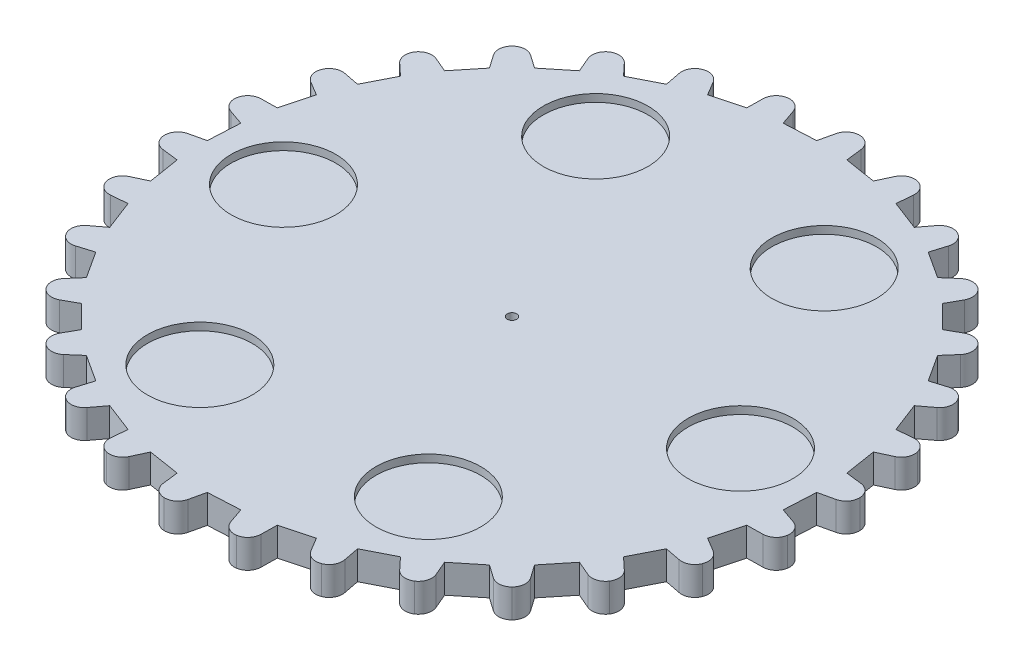
SolidWorks part; units mm, degrees
ref_plane "Front Plane" through (0, 0, 0) normal (0, 0, 1) x (1, 0, 0)
ref_plane "Top Plane" through (0, 0, 0) normal (0, 1, 0) x (1, 0, 0)
ref_plane "Right Plane" through (0, 0, 0) normal (1, 0, 0) x (0, 0, -1)
sketch "Sketch2" plane through (0, 0, 0) normal (0, 1, 0) x (1, 0, 0)
  line L0 (0, 0) -> (0, 203.2)
  line L1 (0, 0) -> (42.2477, 198.7596)
  line L2 (0, 203.2) -> (2.4314, 213.7315)
  line L3 (11.5588, 220.6095) -> (11.5645, 220.6092)
  line L4 (19.923, 212.8148) -> (21.2402, 202.0868)
  line L5 (0, 0) -> (21.2402, 202.0868)
  line L6 (21.2402, 202.0868) -> (42.2477, 198.7596)
  line L7 (57.1735, 213.3854) -> (57.179, 213.3839)
  line L8 (42.2477, 198.7596) -> (46.8155, 208.5554)
  line L9 (63.7343, 204.0221) -> (62.7923, 193.2547)
  line L10 (62.7923, 193.2547) -> (82.6489, 185.6324)
  line L11 (100.2894, 196.8354) -> (100.2945, 196.8328)
  line L12 (82.6489, 185.6324) -> (89.1536, 194.2645)
  line L13 (104.7601, 186.3126) -> (101.6, 175.9764)
  line L14 (101.6, 175.9764) -> (119.438, 164.3923)
  line L15 (139.0223, 171.6827) -> (139.0267, 171.6791)
  line L16 (119.438, 164.3923) -> (127.5952, 171.4833)
  line L17 (141.2074, 160.4604) -> (135.9673, 151.007)
  line L18 (135.9673, 151.007) -> (151.007, 135.9673)
  line L19 (171.6791, 139.0267) -> (171.6827, 139.0223)
  line L20 (151.007, 135.9673) -> (160.4604, 141.2074)
  line L21 (171.4833, 127.5952) -> (164.3923, 119.438)
  line L22 (164.3923, 119.438) -> (175.9764, 101.6)
  line L23 (196.8328, 100.2945) -> (196.8354, 100.2894)
  line L24 (175.9764, 101.6) -> (186.3126, 104.7601)
  line L25 (194.2645, 89.1536) -> (185.6324, 82.6489)
  line L26 (185.6324, 82.6489) -> (193.2547, 62.7923)
  line L27 (213.3839, 57.179) -> (213.3854, 57.1735)
  line L28 (193.2547, 62.7923) -> (204.0221, 63.7343)
  line L29 (208.5554, 46.8155) -> (198.7596, 42.2477)
  line L30 (198.7596, 42.2477) -> (202.0868, 21.2402)
  line L31 (220.6092, 11.5645) -> (220.6095, 11.5588)
  line L32 (202.0868, 21.2402) -> (212.8148, 19.923)
  line L33 (213.7315, 2.4314) -> (203.2, 0)
  line L34 (203.2, 0) -> (202.0868, -21.2402)
  line L35 (218.1927, -34.5554) -> (218.1918, -34.5611)
  line L36 (202.0868, -21.2402) -> (212.3065, -24.7591)
  line L37 (209.5664, -42.059) -> (198.7596, -42.2477)
  line L38 (198.7596, -42.2477) -> (193.2547, -62.7923)
  line L39 (206.2402, -79.1652) -> (206.2382, -79.1705)
  line L40 (193.2547, -62.7923) -> (202.5194, -68.359)
  line L41 (196.2424, -84.7112) -> (185.6324, -82.6489)
  line L42 (185.6324, -82.6489) -> (175.9764, -101.6)
  line L43 (185.274, -120.315) -> (185.2709, -120.3197)
  line L44 (175.9764, -101.6) -> (183.8812, -108.9714)
  line L45 (174.3415, -123.6612) -> (164.3923, -119.438)
  line L46 (164.3923, -119.438) -> (151.007, -135.9673)
  line L47 (156.2104, -156.2064) -> (156.2064, -156.2104)
  line L48 (151.007, -135.9673) -> (157.2065, -144.8211)
  line L49 (144.8211, -157.2065) -> (135.9673, -151.007)
  line L50 (135.9673, -151.007) -> (119.438, -164.3923)
  line L51 (120.3197, -185.2709) -> (120.315, -185.274)
  line L52 (119.438, -164.3923) -> (123.6612, -174.3415)
  line L53 (108.9714, -183.8812) -> (101.6, -175.9764)
  line L54 (101.6, -175.9764) -> (82.6489, -185.6324)
  line L55 (79.1705, -206.2382) -> (79.1652, -206.2402)
  line L56 (82.6489, -185.6324) -> (84.7112, -196.2424)
  line L57 (68.359, -202.5194) -> (62.7923, -193.2547)
  line L58 (62.7923, -193.2547) -> (42.2477, -198.7596)
  line L59 (34.5611, -218.1918) -> (34.5554, -218.1927)
  line L60 (42.2477, -198.7596) -> (42.059, -209.5664)
  line L61 (24.7591, -212.3065) -> (21.2402, -202.0868)
  line L62 (21.2402, -202.0868) -> (0, -203.2)
  line L63 (-11.5588, -220.6095) -> (-11.5645, -220.6092)
  line L64 (0, -203.2) -> (-2.4314, -213.7315)
  line L65 (-19.923, -212.8148) -> (-21.2402, -202.0868)
  line L66 (-21.2402, -202.0868) -> (-42.2477, -198.7596)
  line L67 (-57.1735, -213.3854) -> (-57.179, -213.3839)
  line L68 (-42.2477, -198.7596) -> (-46.8155, -208.5554)
  line L69 (-63.7343, -204.0221) -> (-62.7923, -193.2547)
  line L70 (-62.7923, -193.2547) -> (-82.6489, -185.6324)
  line L71 (-100.2894, -196.8354) -> (-100.2945, -196.8328)
  line L72 (-82.6489, -185.6324) -> (-89.1536, -194.2645)
  line L73 (-104.7601, -186.3126) -> (-101.6, -175.9764)
  line L74 (-101.6, -175.9764) -> (-119.438, -164.3923)
  line L75 (-139.0223, -171.6827) -> (-139.0267, -171.6791)
  line L76 (-119.438, -164.3923) -> (-127.5952, -171.4833)
  line L77 (-141.2074, -160.4604) -> (-135.9673, -151.007)
  line L78 (-135.9673, -151.007) -> (-151.007, -135.9673)
  line L79 (-171.6791, -139.0267) -> (-171.6827, -139.0223)
  line L80 (-151.007, -135.9673) -> (-160.4604, -141.2074)
  line L81 (-171.4833, -127.5952) -> (-164.3923, -119.438)
  line L82 (-164.3923, -119.438) -> (-175.9764, -101.6)
  line L83 (-196.8328, -100.2945) -> (-196.8354, -100.2894)
  line L84 (-175.9764, -101.6) -> (-186.3126, -104.7601)
  line L85 (-194.2645, -89.1536) -> (-185.6324, -82.6489)
  line L86 (-185.6324, -82.6489) -> (-193.2547, -62.7923)
  line L87 (-213.3839, -57.179) -> (-213.3854, -57.1735)
  line L88 (-193.2547, -62.7923) -> (-204.0221, -63.7343)
  line L89 (-208.5554, -46.8155) -> (-198.7596, -42.2477)
  line L90 (-198.7596, -42.2477) -> (-202.0868, -21.2402)
  line L91 (-220.6092, -11.5645) -> (-220.6095, -11.5588)
  line L92 (-202.0868, -21.2402) -> (-212.8148, -19.923)
  line L93 (-213.7315, -2.4314) -> (-203.2, 0)
  line L94 (-203.2, 0) -> (-202.0868, 21.2402)
  line L95 (-218.1927, 34.5554) -> (-218.1918, 34.5611)
  line L96 (-202.0868, 21.2402) -> (-212.3065, 24.7591)
  line L97 (-209.5664, 42.059) -> (-198.7596, 42.2477)
  line L98 (-198.7596, 42.2477) -> (-193.2547, 62.7923)
  line L99 (-206.2402, 79.1652) -> (-206.2382, 79.1705)
  line L100 (-193.2547, 62.7923) -> (-202.5194, 68.359)
  line L101 (-196.2424, 84.7112) -> (-185.6324, 82.6489)
  line L102 (-185.6324, 82.6489) -> (-175.9764, 101.6)
  line L103 (-185.274, 120.315) -> (-185.2709, 120.3197)
  line L104 (-175.9764, 101.6) -> (-183.8812, 108.9714)
  line L105 (-174.3415, 123.6612) -> (-164.3923, 119.438)
  line L106 (-164.3923, 119.438) -> (-151.007, 135.9673)
  line L107 (-156.2104, 156.2064) -> (-156.2064, 156.2104)
  line L108 (-151.007, 135.9673) -> (-157.2065, 144.8211)
  line L109 (-144.8211, 157.2065) -> (-135.9673, 151.007)
  line L110 (-135.9673, 151.007) -> (-119.438, 164.3923)
  line L111 (-120.3197, 185.2709) -> (-120.315, 185.274)
  line L112 (-119.438, 164.3923) -> (-123.6612, 174.3415)
  line L113 (-108.9714, 183.8812) -> (-101.6, 175.9764)
  line L114 (-101.6, 175.9764) -> (-82.6489, 185.6324)
  line L115 (-79.1705, 206.2382) -> (-79.1652, 206.2402)
  line L116 (-82.6489, 185.6324) -> (-84.7112, 196.2424)
  line L117 (-68.359, 202.5194) -> (-62.7923, 193.2547)
  line L118 (-62.7923, 193.2547) -> (-42.2477, 198.7596)
  line L119 (-34.5611, 218.1918) -> (-34.5554, 218.1927)
  line L120 (-42.2477, 198.7596) -> (-42.059, 209.5664)
  line L121 (-24.7591, 212.3065) -> (-21.2402, 202.0868)
  line L122 (-21.2402, 202.0868) -> (0, 203.2)
  arc A1 (11.5645, 220.6092) -> (19.923, 212.8148) centre (11.0992, 211.7314) cw
  arc A2 (11.5588, 220.6095) -> (2.4314, 213.7315) centre (11.0935, 211.7317) ccw
  arc A3 (57.1735, 213.3854) -> (46.8155, 208.5554) centre (54.8726, 204.7983) ccw
  arc A4 (57.179, 213.3839) -> (63.7343, 204.0221) centre (54.8781, 204.7969) cw
  arc A5 (100.2894, 196.8354) -> (89.1536, 194.2645) centre (96.2535, 188.9144) ccw
  arc A6 (100.2945, 196.8328) -> (104.7601, 186.3126) centre (96.2586, 188.9118) cw
  arc A7 (139.0223, 171.6827) -> (127.5952, 171.4833) centre (133.4276, 164.7739) ccw
  arc A8 (139.0267, 171.6791) -> (141.2074, 160.4604) centre (133.432, 164.7703) cw
  arc A9 (171.6791, 139.0267) -> (160.4604, 141.2074) centre (164.7703, 133.432) ccw
  arc A10 (171.6827, 139.0223) -> (171.4833, 127.5952) centre (164.7739, 133.4276) cw
  arc A11 (196.8328, 100.2945) -> (186.3126, 104.7601) centre (188.9118, 96.2586) ccw
  arc A12 (196.8354, 100.2894) -> (194.2645, 89.1536) centre (188.9144, 96.2535) cw
  arc A13 (213.3839, 57.179) -> (204.0221, 63.7343) centre (204.7969, 54.8781) ccw
  arc A14 (213.3854, 57.1735) -> (208.5554, 46.8155) centre (204.7983, 54.8726) cw
  arc A15 (220.6092, 11.5645) -> (212.8148, 19.923) centre (211.7314, 11.0992) ccw
  arc A16 (220.6095, 11.5588) -> (213.7315, 2.4314) centre (211.7317, 11.0935) cw
  arc A17 (218.1927, -34.5554) -> (212.3065, -24.7591) centre (209.4122, -33.1647) ccw
  arc A18 (218.1918, -34.5611) -> (209.5664, -42.059) centre (209.4113, -33.1704) cw
  arc A19 (206.2402, -79.1652) -> (202.5194, -68.359) centre (197.9407, -75.9793) ccw
  arc A20 (206.2382, -79.1705) -> (196.2424, -84.7112) centre (197.9386, -75.9846) cw
  arc A21 (185.274, -120.315) -> (183.8812, -108.9714) centre (177.8182, -115.4731) ccw
  arc A22 (185.2709, -120.3197) -> (174.3415, -123.6612) centre (177.8151, -115.4779) cw
  arc A23 (156.2104, -156.2064) -> (157.2065, -144.8211) centre (149.9243, -149.9202) ccw
  arc A24 (156.2064, -156.2104) -> (144.8211, -157.2065) centre (149.9202, -149.9243) cw
  arc A25 (120.3197, -185.2709) -> (123.6612, -174.3415) centre (115.4779, -177.8151) ccw
  arc A26 (120.315, -185.274) -> (108.9714, -183.8812) centre (115.4731, -177.8182) cw
  arc A27 (79.1705, -206.2382) -> (84.7112, -196.2424) centre (75.9846, -197.9386) ccw
  arc A28 (79.1652, -206.2402) -> (68.359, -202.5194) centre (75.9793, -197.9407) cw
  arc A29 (34.5611, -218.1918) -> (42.059, -209.5664) centre (33.1704, -209.4113) ccw
  arc A30 (34.5554, -218.1927) -> (24.7591, -212.3065) centre (33.1647, -209.4122) cw
  arc A31 (-11.5588, -220.6095) -> (-2.4314, -213.7315) centre (-11.0935, -211.7317) ccw
  arc A32 (-11.5645, -220.6092) -> (-19.923, -212.8148) centre (-11.0992, -211.7314) cw
  arc A33 (-57.1735, -213.3854) -> (-46.8155, -208.5554) centre (-54.8726, -204.7983) ccw
  arc A34 (-57.179, -213.3839) -> (-63.7343, -204.0221) centre (-54.8781, -204.7969) cw
  arc A35 (-100.2894, -196.8354) -> (-89.1536, -194.2645) centre (-96.2535, -188.9144) ccw
  arc A36 (-100.2945, -196.8328) -> (-104.7601, -186.3126) centre (-96.2586, -188.9118) cw
  arc A37 (-139.0223, -171.6827) -> (-127.5952, -171.4833) centre (-133.4276, -164.7739) ccw
  arc A38 (-139.0267, -171.6791) -> (-141.2074, -160.4604) centre (-133.432, -164.7703) cw
  arc A39 (-171.6791, -139.0267) -> (-160.4604, -141.2074) centre (-164.7703, -133.432) ccw
  arc A40 (-171.6827, -139.0223) -> (-171.4833, -127.5952) centre (-164.7739, -133.4276) cw
  arc A41 (-196.8328, -100.2945) -> (-186.3126, -104.7601) centre (-188.9118, -96.2586) ccw
  arc A42 (-196.8354, -100.2894) -> (-194.2645, -89.1536) centre (-188.9144, -96.2535) cw
  arc A43 (-213.3839, -57.179) -> (-204.0221, -63.7343) centre (-204.7969, -54.8781) ccw
  arc A44 (-213.3854, -57.1735) -> (-208.5554, -46.8155) centre (-204.7983, -54.8726) cw
  arc A45 (-220.6092, -11.5645) -> (-212.8148, -19.923) centre (-211.7314, -11.0992) ccw
  arc A46 (-220.6095, -11.5588) -> (-213.7315, -2.4314) centre (-211.7317, -11.0935) cw
  arc A47 (-218.1927, 34.5554) -> (-212.3065, 24.7591) centre (-209.4122, 33.1647) ccw
  arc A48 (-218.1918, 34.5611) -> (-209.5664, 42.059) centre (-209.4113, 33.1704) cw
  arc A49 (-206.2402, 79.1652) -> (-202.5194, 68.359) centre (-197.9407, 75.9793) ccw
  arc A50 (-206.2382, 79.1705) -> (-196.2424, 84.7112) centre (-197.9386, 75.9846) cw
  arc A51 (-185.274, 120.315) -> (-183.8812, 108.9714) centre (-177.8182, 115.4731) ccw
  arc A52 (-185.2709, 120.3197) -> (-174.3415, 123.6612) centre (-177.8151, 115.4779) cw
  arc A53 (-156.2104, 156.2064) -> (-157.2065, 144.8211) centre (-149.9243, 149.9202) ccw
  arc A54 (-156.2064, 156.2104) -> (-144.8211, 157.2065) centre (-149.9202, 149.9243) cw
  arc A55 (-120.3197, 185.2709) -> (-123.6612, 174.3415) centre (-115.4779, 177.8151) ccw
  arc A56 (-120.315, 185.274) -> (-108.9714, 183.8812) centre (-115.4731, 177.8182) cw
  arc A57 (-79.1705, 206.2382) -> (-84.7112, 196.2424) centre (-75.9846, 197.9386) ccw
  arc A58 (-79.1652, 206.2402) -> (-68.359, 202.5194) centre (-75.9793, 197.9407) cw
  arc A59 (-34.5611, 218.1918) -> (-42.059, 209.5664) centre (-33.1704, 209.4113) ccw
  arc A60 (-34.5554, 218.1927) -> (-24.7591, 212.3065) centre (-33.1647, 209.4122) cw
  point P305 (0, 0)
  dimension "D8" = 8.89
  dimension "D2" = 12
  dimension "D3" = 6
  dimension "D4" = 87
  dimension "D5" = 0
  dimension "D6" = 80
  dimension "D7" = 80
  dimension "D9" = 30
extrude "Boss-Extrude2" add sketch "Sketch2" along normal blind 19.05 contours L3 A2 L2 L0 L5 L4 A1 | L6 L5 L1 | A60 L119 A59 L120 L118 L117 A58 L115 A57 L116 L114 L113 A56 L111 A55 L112 L110 L109 A54 L107 A53 L108 L106 L105 A52 L103 A51 L104 L102 L101 A50 L99 A49 L100 L98 L97 A48 L95 A47 L96 L94 L93 A46 L91 A45 L92 L90 L89 A44 L87 A43
sketch "Sketch3" plane through (0, 19.05, 0) normal (0, 1, 0) x (1, 0, 0)
  circle A0 centre (-152.4, 0) radius 34.925
  circle A1 centre (-76.2, 131.9823) radius 34.925
  circle A2 centre (76.2, 131.9823) radius 34.925
  circle A3 centre (152.4, 0) radius 34.925
  circle A4 centre (76.2, -131.9823) radius 34.925
  circle A5 centre (-76.2, -131.9823) radius 34.925
  point P16 (0, 0)
  dimension "D2" = 69.85
  dimension "D1" = 152.4
  dimension "D3" = 6
extrude "Cut-Extrude1" cut sketch "Sketch3" against normal blind 5.08
sketch "Sketch4" plane through (0, 19.05, 0) normal (0, 1, 0) x (1, 0, 0)
  circle A0 centre (0, 0) radius 3.175
  dimension "D1" = 6.35
extrude "Cut-Extrude2" cut sketch "Sketch4" against normal through all
sketch "Sketch5" plane through (0, 19.05, 0) normal (0, 1, 0) x (1, 0, 0)
  line L120 (46.8155, 208.5554) -> (42.2477, 198.7596)
  line L121 (42.2477, 198.7596) -> (21.2402, 202.0868)
  line L122 (21.2402, 202.0868) -> (19.923, 212.8148)
  line L123 (11.5645, 220.6092) -> (11.5588, 220.6095)
  line L124 (2.4314, 213.7315) -> (0, 203.2)
  line L125 (0, 203.2) -> (-21.2402, 202.0868)
  line L126 (-21.2402, 202.0868) -> (-24.7591, 212.3065)
  line L127 (-34.5554, 218.1927) -> (-34.5611, 218.1918)
  line L128 (-42.059, 209.5664) -> (-42.2477, 198.7596)
  line L129 (-42.2477, 198.7596) -> (-62.7923, 193.2547)
  line L130 (-62.7923, 193.2547) -> (-68.359, 202.5194)
  line L131 (-79.1652, 206.2402) -> (-79.1705, 206.2382)
  line L132 (-84.7112, 196.2424) -> (-82.6489, 185.6324)
  line L133 (-82.6489, 185.6324) -> (-101.6, 175.9764)
  line L134 (-101.6, 175.9764) -> (-108.9714, 183.8812)
  line L135 (-120.315, 185.274) -> (-120.3197, 185.2709)
  line L136 (-123.6612, 174.3415) -> (-119.438, 164.3923)
  line L137 (-119.438, 164.3923) -> (-135.9673, 151.007)
  line L138 (-135.9673, 151.007) -> (-144.8211, 157.2065)
  line L139 (-156.2064, 156.2104) -> (-156.2104, 156.2064)
  line L140 (-157.2065, 144.8211) -> (-151.007, 135.9673)
  line L141 (-151.007, 135.9673) -> (-164.3923, 119.438)
  line L142 (-164.3923, 119.438) -> (-174.3415, 123.6612)
  line L143 (-185.2709, 120.3197) -> (-185.274, 120.315)
  line L144 (-183.8812, 108.9714) -> (-175.9764, 101.6)
  line L145 (-175.9764, 101.6) -> (-185.6324, 82.6489)
  line L146 (-185.6324, 82.6489) -> (-196.2424, 84.7112)
  line L147 (-206.2382, 79.1705) -> (-206.2402, 79.1652)
  line L148 (-202.5194, 68.359) -> (-193.2547, 62.7923)
  line L149 (-193.2547, 62.7923) -> (-198.7596, 42.2477)
  line L150 (-198.7596, 42.2477) -> (-209.5664, 42.059)
  line L151 (-218.1918, 34.5611) -> (-218.1927, 34.5554)
  line L152 (-212.3065, 24.7591) -> (-202.0868, 21.2402)
  line L153 (-202.0868, 21.2402) -> (-203.2, 0)
  line L154 (-203.2, 0) -> (-213.7315, -2.4314)
  line L155 (-220.6095, -11.5588) -> (-220.6092, -11.5645)
  line L156 (-212.8148, -19.923) -> (-202.0868, -21.2402)
  line L157 (-202.0868, -21.2402) -> (-198.7596, -42.2477)
  line L158 (-198.7596, -42.2477) -> (-208.5554, -46.8155)
  line L159 (-213.3854, -57.1735) -> (-213.3839, -57.179)
  line L160 (-204.0221, -63.7343) -> (-193.2547, -62.7923)
  line L161 (-193.2547, -62.7923) -> (-185.6324, -82.6489)
  line L162 (-185.6324, -82.6489) -> (-194.2645, -89.1536)
  line L163 (-196.8354, -100.2894) -> (-196.8328, -100.2945)
  line L164 (-186.3126, -104.7601) -> (-175.9764, -101.6)
  line L165 (-175.9764, -101.6) -> (-164.3923, -119.438)
  line L166 (-164.3923, -119.438) -> (-171.4833, -127.5952)
  line L167 (-171.6827, -139.0223) -> (-171.6791, -139.0267)
  line L168 (-160.4604, -141.2074) -> (-151.007, -135.9673)
  line L169 (-151.007, -135.9673) -> (-135.9673, -151.007)
  line L170 (-135.9673, -151.007) -> (-141.2074, -160.4604)
  line L171 (-139.0267, -171.6791) -> (-139.0223, -171.6827)
  line L172 (-127.5952, -171.4833) -> (-119.438, -164.3923)
  line L173 (-119.438, -164.3923) -> (-101.6, -175.9764)
  line L174 (-101.6, -175.9764) -> (-104.7601, -186.3126)
  line L175 (-100.2945, -196.8328) -> (-100.2894, -196.8354)
  line L176 (-89.1536, -194.2645) -> (-82.6489, -185.6324)
  line L177 (-82.6489, -185.6324) -> (-62.7923, -193.2547)
  line L178 (-62.7923, -193.2547) -> (-63.7343, -204.0221)
  line L179 (-57.179, -213.3839) -> (-57.1735, -213.3854)
  line L180 (-46.8155, -208.5554) -> (-42.2477, -198.7596)
  line L181 (-42.2477, -198.7596) -> (-21.2402, -202.0868)
  line L182 (-21.2402, -202.0868) -> (-19.923, -212.8148)
  line L183 (-11.5645, -220.6092) -> (-11.5588, -220.6095)
  line L184 (-2.4314, -213.7315) -> (0, -203.2)
  line L185 (0, -203.2) -> (21.2402, -202.0868)
  line L186 (21.2402, -202.0868) -> (24.7591, -212.3065)
  line L187 (34.5554, -218.1927) -> (34.5611, -218.1918)
  line L188 (42.059, -209.5664) -> (42.2477, -198.7596)
  line L189 (42.2477, -198.7596) -> (62.7923, -193.2547)
  line L190 (62.7923, -193.2547) -> (68.359, -202.5194)
  line L191 (79.1652, -206.2402) -> (79.1705, -206.2382)
  line L192 (84.7112, -196.2424) -> (82.6489, -185.6324)
  line L193 (82.6489, -185.6324) -> (101.6, -175.9764)
  line L194 (101.6, -175.9764) -> (108.9714, -183.8812)
  line L195 (120.315, -185.274) -> (120.3197, -185.2709)
  line L196 (123.6612, -174.3415) -> (119.438, -164.3923)
  line L197 (119.438, -164.3923) -> (135.9673, -151.007)
  line L198 (135.9673, -151.007) -> (144.8211, -157.2065)
  line L199 (156.2064, -156.2104) -> (156.2104, -156.2064)
  line L200 (157.2065, -144.8211) -> (151.007, -135.9673)
  line L201 (151.007, -135.9673) -> (164.3923, -119.438)
  line L202 (164.3923, -119.438) -> (174.3415, -123.6612)
  line L203 (185.2709, -120.3197) -> (185.274, -120.315)
  line L204 (183.8812, -108.9714) -> (175.9764, -101.6)
  line L205 (175.9764, -101.6) -> (185.6324, -82.6489)
  line L206 (185.6324, -82.6489) -> (196.2424, -84.7112)
  line L207 (206.2382, -79.1705) -> (206.2402, -79.1652)
  line L208 (202.5194, -68.359) -> (193.2547, -62.7923)
  line L209 (193.2547, -62.7923) -> (198.7596, -42.2477)
  line L210 (198.7596, -42.2477) -> (209.5664, -42.059)
  line L211 (218.1918, -34.5611) -> (218.1927, -34.5554)
  line L212 (212.3065, -24.7591) -> (202.0868, -21.2402)
  line L213 (202.0868, -21.2402) -> (203.2, 0)
  line L214 (203.2, 0) -> (213.7315, 2.4314)
  line L215 (220.6095, 11.5588) -> (220.6092, 11.5645)
  line L216 (212.8148, 19.923) -> (202.0868, 21.2402)
  line L217 (202.0868, 21.2402) -> (198.7596, 42.2477)
  line L218 (198.7596, 42.2477) -> (208.5554, 46.8155)
  line L219 (213.3854, 57.1735) -> (213.3839, 57.179)
  line L220 (204.0221, 63.7343) -> (193.2547, 62.7923)
  line L221 (193.2547, 62.7923) -> (185.6324, 82.6489)
  line L222 (185.6324, 82.6489) -> (194.2645, 89.1536)
  line L223 (196.8354, 100.2894) -> (196.8328, 100.2945)
  line L224 (186.3126, 104.7601) -> (175.9764, 101.6)
  line L225 (175.9764, 101.6) -> (164.3923, 119.438)
  line L226 (164.3923, 119.438) -> (171.4833, 127.5952)
  line L227 (171.6827, 139.0223) -> (171.6791, 139.0267)
  line L228 (160.4604, 141.2074) -> (151.007, 135.9673)
  line L229 (151.007, 135.9673) -> (135.9673, 151.007)
  line L230 (135.9673, 151.007) -> (141.2074, 160.4604)
  line L231 (139.0267, 171.6791) -> (139.0223, 171.6827)
  line L232 (127.5952, 171.4833) -> (119.438, 164.3923)
  line L233 (119.438, 164.3923) -> (101.6, 175.9764)
  line L234 (101.6, 175.9764) -> (104.7601, 186.3126)
  line L235 (100.2945, 196.8328) -> (100.2894, 196.8354)
  line L236 (89.1536, 194.2645) -> (82.6489, 185.6324)
  line L237 (82.6489, 185.6324) -> (62.7923, 193.2547)
  line L238 (62.7923, 193.2547) -> (63.7343, 204.0221)
  line L239 (57.179, 213.3839) -> (57.1735, 213.3854)
  line L240 (46.8155, 208.5554) -> (42.2477, 198.7596)
  line L241 (42.2477, 198.7596) -> (21.2402, 202.0868)
  line L242 (21.2402, 202.0868) -> (19.923, 212.8148)
  line L243 (11.5645, 220.6092) -> (11.5588, 220.6095)
  line L244 (2.4314, 213.7315) -> (0, 203.2)
  line L245 (0, 203.2) -> (-21.2402, 202.0868)
  line L246 (-21.2402, 202.0868) -> (-24.7591, 212.3065)
  line L247 (-34.5554, 218.1927) -> (-34.5611, 218.1918)
  line L248 (-42.059, 209.5664) -> (-42.2477, 198.7596)
  line L249 (-42.2477, 198.7596) -> (-62.7923, 193.2547)
  line L250 (-62.7923, 193.2547) -> (-68.359, 202.5194)
  line L251 (-79.1652, 206.2402) -> (-79.1705, 206.2382)
  line L252 (-84.7112, 196.2424) -> (-82.6489, 185.6324)
  line L253 (-82.6489, 185.6324) -> (-101.6, 175.9764)
  line L254 (-101.6, 175.9764) -> (-108.9714, 183.8812)
  line L255 (-120.315, 185.274) -> (-120.3197, 185.2709)
  line L256 (-123.6612, 174.3415) -> (-119.438, 164.3923)
  line L257 (-119.438, 164.3923) -> (-135.9673, 151.007)
  line L258 (-135.9673, 151.007) -> (-144.8211, 157.2065)
  line L259 (-156.2064, 156.2104) -> (-156.2104, 156.2064)
  line L260 (-157.2065, 144.8211) -> (-151.007, 135.9673)
  line L261 (-151.007, 135.9673) -> (-164.3923, 119.438)
  line L262 (-164.3923, 119.438) -> (-174.3415, 123.6612)
  line L263 (-185.2709, 120.3197) -> (-185.274, 120.315)
  line L264 (-183.8812, 108.9714) -> (-175.9764, 101.6)
  line L265 (-175.9764, 101.6) -> (-185.6324, 82.6489)
  line L266 (-185.6324, 82.6489) -> (-196.2424, 84.7112)
  line L267 (-206.2382, 79.1705) -> (-206.2402, 79.1652)
  line L268 (-202.5194, 68.359) -> (-193.2547, 62.7923)
  line L269 (-193.2547, 62.7923) -> (-198.7596, 42.2477)
  line L270 (-198.7596, 42.2477) -> (-209.5664, 42.059)
  line L271 (-218.1918, 34.5611) -> (-218.1927, 34.5554)
  line L272 (-212.3065, 24.7591) -> (-202.0868, 21.2402)
  line L273 (-202.0868, 21.2402) -> (-203.2, 0)
  line L274 (-203.2, 0) -> (-213.7315, -2.4314)
  line L275 (-220.6095, -11.5588) -> (-220.6092, -11.5645)
  line L276 (-212.8148, -19.923) -> (-202.0868, -21.2402)
  line L277 (-202.0868, -21.2402) -> (-198.7596, -42.2477)
  line L278 (-198.7596, -42.2477) -> (-208.5554, -46.8155)
  line L279 (-213.3854, -57.1735) -> (-213.3839, -57.179)
  line L280 (-204.0221, -63.7343) -> (-193.2547, -62.7923)
  line L281 (-193.2547, -62.7923) -> (-185.6324, -82.6489)
  line L282 (-185.6324, -82.6489) -> (-194.2645, -89.1536)
  line L283 (-196.8354, -100.2894) -> (-196.8328, -100.2945)
  line L284 (-186.3126, -104.7601) -> (-175.9764, -101.6)
  line L285 (-175.9764, -101.6) -> (-164.3923, -119.438)
  line L286 (-164.3923, -119.438) -> (-171.4833, -127.5952)
  line L287 (-171.6827, -139.0223) -> (-171.6791, -139.0267)
  line L288 (-160.4604, -141.2074) -> (-151.007, -135.9673)
  line L289 (-151.007, -135.9673) -> (-135.9673, -151.007)
  line L290 (-135.9673, -151.007) -> (-141.2074, -160.4604)
  line L291 (-139.0267, -171.6791) -> (-139.0223, -171.6827)
  line L292 (-127.5952, -171.4833) -> (-119.438, -164.3923)
  line L293 (-119.438, -164.3923) -> (-101.6, -175.9764)
  line L294 (-101.6, -175.9764) -> (-104.7601, -186.3126)
  line L295 (-100.2945, -196.8328) -> (-100.2894, -196.8354)
  line L296 (-89.1536, -194.2645) -> (-82.6489, -185.6324)
  line L297 (-82.6489, -185.6324) -> (-62.7923, -193.2547)
  line L298 (-62.7923, -193.2547) -> (-63.7343, -204.0221)
  line L299 (-57.179, -213.3839) -> (-57.1735, -213.3854)
  line L300 (-46.8155, -208.5554) -> (-42.2477, -198.7596)
  line L301 (-42.2477, -198.7596) -> (-21.2402, -202.0868)
  line L302 (-21.2402, -202.0868) -> (-19.923, -212.8148)
  line L303 (-11.5645, -220.6092) -> (-11.5588, -220.6095)
  line L304 (-2.4314, -213.7315) -> (0, -203.2)
  line L305 (0, -203.2) -> (21.2402, -202.0868)
  line L306 (21.2402, -202.0868) -> (24.7591, -212.3065)
  line L307 (34.5554, -218.1927) -> (34.5611, -218.1918)
  line L308 (42.059, -209.5664) -> (42.2477, -198.7596)
  line L309 (42.2477, -198.7596) -> (62.7923, -193.2547)
  line L310 (62.7923, -193.2547) -> (68.359, -202.5194)
  line L311 (79.1652, -206.2402) -> (79.1705, -206.2382)
  line L312 (84.7112, -196.2424) -> (82.6489, -185.6324)
  line L313 (82.6489, -185.6324) -> (101.6, -175.9764)
  line L314 (101.6, -175.9764) -> (108.9714, -183.8812)
  line L315 (120.315, -185.274) -> (120.3197, -185.2709)
  line L316 (123.6612, -174.3415) -> (119.438, -164.3923)
  line L317 (119.438, -164.3923) -> (135.9673, -151.007)
  line L318 (135.9673, -151.007) -> (144.8211, -157.2065)
  line L319 (156.2064, -156.2104) -> (156.2104, -156.2064)
  line L320 (157.2065, -144.8211) -> (151.007, -135.9673)
  line L321 (151.007, -135.9673) -> (164.3923, -119.438)
  line L322 (164.3923, -119.438) -> (174.3415, -123.6612)
  line L323 (185.2709, -120.3197) -> (185.274, -120.315)
  line L324 (183.8812, -108.9714) -> (175.9764, -101.6)
  line L325 (175.9764, -101.6) -> (185.6324, -82.6489)
  line L326 (185.6324, -82.6489) -> (196.2424, -84.7112)
  line L327 (206.2382, -79.1705) -> (206.2402, -79.1652)
  line L328 (202.5194, -68.359) -> (193.2547, -62.7923)
  line L329 (193.2547, -62.7923) -> (198.7596, -42.2477)
  line L330 (198.7596, -42.2477) -> (209.5664, -42.059)
  line L331 (218.1918, -34.5611) -> (218.1927, -34.5554)
  line L332 (212.3065, -24.7591) -> (202.0868, -21.2402)
  line L333 (202.0868, -21.2402) -> (203.2, 0)
  line L334 (203.2, 0) -> (213.7315, 2.4314)
  line L335 (220.6095, 11.5588) -> (220.6092, 11.5645)
  line L336 (212.8148, 19.923) -> (202.0868, 21.2402)
  line L337 (202.0868, 21.2402) -> (198.7596, 42.2477)
  line L338 (198.7596, 42.2477) -> (208.5554, 46.8155)
  line L339 (213.3854, 57.1735) -> (213.3839, 57.179)
  line L340 (204.0221, 63.7343) -> (193.2547, 62.7923)
  line L341 (193.2547, 62.7923) -> (185.6324, 82.6489)
  line L342 (185.6324, 82.6489) -> (194.2645, 89.1536)
  line L343 (196.8354, 100.2894) -> (196.8328, 100.2945)
  line L344 (186.3126, 104.7601) -> (175.9764, 101.6)
  line L345 (175.9764, 101.6) -> (164.3923, 119.438)
  line L346 (164.3923, 119.438) -> (171.4833, 127.5952)
  line L347 (171.6827, 139.0223) -> (171.6791, 139.0267)
  line L348 (160.4604, 141.2074) -> (151.007, 135.9673)
  line L349 (151.007, 135.9673) -> (135.9673, 151.007)
  line L350 (135.9673, 151.007) -> (141.2074, 160.4604)
  line L351 (139.0267, 171.6791) -> (139.0223, 171.6827)
  line L352 (127.5952, 171.4833) -> (119.438, 164.3923)
  line L353 (119.438, 164.3923) -> (101.6, 175.9764)
  line L354 (101.6, 175.9764) -> (104.7601, 186.3126)
  line L355 (100.2945, 196.8328) -> (100.2894, 196.8354)
  line L356 (89.1536, 194.2645) -> (82.6489, 185.6324)
  line L357 (82.6489, 185.6324) -> (62.7923, 193.2547)
  line L358 (62.7923, 193.2547) -> (63.7343, 204.0221)
  line L359 (57.179, 213.3839) -> (57.1735, 213.3854)
  arc A61 (19.923, 212.8148) -> (11.5645, 220.6092) centre (11.0992, 211.7314) ccw
  arc A62 (11.5588, 220.6095) -> (2.4314, 213.7315) centre (11.0935, 211.7317) ccw
  arc A63 (-24.7591, 212.3065) -> (-34.5554, 218.1927) centre (-33.1647, 209.4122) ccw
  arc A64 (-34.5611, 218.1918) -> (-42.059, 209.5664) centre (-33.1704, 209.4113) ccw
  arc A65 (-68.359, 202.5194) -> (-79.1652, 206.2402) centre (-75.9793, 197.9407) ccw
  arc A66 (-79.1705, 206.2382) -> (-84.7112, 196.2424) centre (-75.9846, 197.9386) ccw
  arc A67 (-108.9714, 183.8812) -> (-120.315, 185.274) centre (-115.4731, 177.8182) ccw
  arc A68 (-120.3197, 185.2709) -> (-123.6612, 174.3415) centre (-115.4779, 177.8151) ccw
  arc A69 (-144.8211, 157.2065) -> (-156.2064, 156.2104) centre (-149.9202, 149.9243) ccw
  arc A70 (-156.2104, 156.2064) -> (-157.2065, 144.8211) centre (-149.9243, 149.9202) ccw
  arc A71 (-174.3415, 123.6612) -> (-185.2709, 120.3197) centre (-177.8151, 115.4779) ccw
  arc A72 (-185.274, 120.315) -> (-183.8812, 108.9714) centre (-177.8182, 115.4731) ccw
  arc A73 (-196.2424, 84.7112) -> (-206.2382, 79.1705) centre (-197.9386, 75.9846) ccw
  arc A74 (-206.2402, 79.1652) -> (-202.5194, 68.359) centre (-197.9407, 75.9793) ccw
  arc A75 (-209.5664, 42.059) -> (-218.1918, 34.5611) centre (-209.4113, 33.1704) ccw
  arc A76 (-218.1927, 34.5554) -> (-212.3065, 24.7591) centre (-209.4122, 33.1647) ccw
  arc A77 (-213.7315, -2.4314) -> (-220.6095, -11.5588) centre (-211.7317, -11.0935) ccw
  arc A78 (-220.6092, -11.5645) -> (-212.8148, -19.923) centre (-211.7314, -11.0992) ccw
  arc A79 (-208.5554, -46.8155) -> (-213.3854, -57.1735) centre (-204.7983, -54.8726) ccw
  arc A80 (-213.3839, -57.179) -> (-204.0221, -63.7343) centre (-204.7969, -54.8781) ccw
  arc A81 (-194.2645, -89.1536) -> (-196.8354, -100.2894) centre (-188.9144, -96.2535) ccw
  arc A82 (-196.8328, -100.2945) -> (-186.3126, -104.7601) centre (-188.9118, -96.2586) ccw
  arc A83 (-171.4833, -127.5952) -> (-171.6827, -139.0223) centre (-164.7739, -133.4276) ccw
  arc A84 (-171.6791, -139.0267) -> (-160.4604, -141.2074) centre (-164.7703, -133.432) ccw
  arc A85 (-141.2074, -160.4604) -> (-139.0267, -171.6791) centre (-133.432, -164.7703) ccw
  arc A86 (-139.0223, -171.6827) -> (-127.5952, -171.4833) centre (-133.4276, -164.7739) ccw
  arc A87 (-104.7601, -186.3126) -> (-100.2945, -196.8328) centre (-96.2586, -188.9118) ccw
  arc A88 (-100.2894, -196.8354) -> (-89.1536, -194.2645) centre (-96.2535, -188.9144) ccw
  arc A89 (-63.7343, -204.0221) -> (-57.179, -213.3839) centre (-54.8781, -204.7969) ccw
  arc A90 (-57.1735, -213.3854) -> (-46.8155, -208.5554) centre (-54.8726, -204.7983) ccw
  arc A91 (-19.923, -212.8148) -> (-11.5645, -220.6092) centre (-11.0992, -211.7314) ccw
  arc A92 (-11.5588, -220.6095) -> (-2.4314, -213.7315) centre (-11.0935, -211.7317) ccw
  arc A93 (24.7591, -212.3065) -> (34.5554, -218.1927) centre (33.1647, -209.4122) ccw
  arc A94 (34.5611, -218.1918) -> (42.059, -209.5664) centre (33.1704, -209.4113) ccw
  arc A95 (68.359, -202.5194) -> (79.1652, -206.2402) centre (75.9793, -197.9407) ccw
  arc A96 (79.1705, -206.2382) -> (84.7112, -196.2424) centre (75.9846, -197.9386) ccw
  arc A97 (108.9714, -183.8812) -> (120.315, -185.274) centre (115.4731, -177.8182) ccw
  arc A98 (120.3197, -185.2709) -> (123.6612, -174.3415) centre (115.4779, -177.8151) ccw
  arc A99 (144.8211, -157.2065) -> (156.2064, -156.2104) centre (149.9202, -149.9243) ccw
  arc A100 (156.2104, -156.2064) -> (157.2065, -144.8211) centre (149.9243, -149.9202) ccw
  arc A101 (174.3415, -123.6612) -> (185.2709, -120.3197) centre (177.8151, -115.4779) ccw
  arc A102 (185.274, -120.315) -> (183.8812, -108.9714) centre (177.8182, -115.4731) ccw
  arc A103 (196.2424, -84.7112) -> (206.2382, -79.1705) centre (197.9386, -75.9846) ccw
  arc A104 (206.2402, -79.1652) -> (202.5194, -68.359) centre (197.9407, -75.9793) ccw
  arc A105 (209.5664, -42.059) -> (218.1918, -34.5611) centre (209.4113, -33.1704) ccw
  arc A106 (218.1927, -34.5554) -> (212.3065, -24.7591) centre (209.4122, -33.1647) ccw
  arc A107 (213.7315, 2.4314) -> (220.6095, 11.5588) centre (211.7317, 11.0935) ccw
  arc A108 (220.6092, 11.5645) -> (212.8148, 19.923) centre (211.7314, 11.0992) ccw
  arc A109 (208.5554, 46.8155) -> (213.3854, 57.1735) centre (204.7983, 54.8726) ccw
  arc A110 (213.3839, 57.179) -> (204.0221, 63.7343) centre (204.7969, 54.8781) ccw
  arc A111 (194.2645, 89.1536) -> (196.8354, 100.2894) centre (188.9144, 96.2535) ccw
  arc A112 (196.8328, 100.2945) -> (186.3126, 104.7601) centre (188.9118, 96.2586) ccw
  arc A113 (171.4833, 127.5952) -> (171.6827, 139.0223) centre (164.7739, 133.4276) ccw
  arc A114 (171.6791, 139.0267) -> (160.4604, 141.2074) centre (164.7703, 133.432) ccw
  arc A115 (141.2074, 160.4604) -> (139.0267, 171.6791) centre (133.432, 164.7703) ccw
  arc A116 (139.0223, 171.6827) -> (127.5952, 171.4833) centre (133.4276, 164.7739) ccw
  arc A117 (104.7601, 186.3126) -> (100.2945, 196.8328) centre (96.2586, 188.9118) ccw
  arc A118 (100.2894, 196.8354) -> (89.1536, 194.2645) centre (96.2535, 188.9144) ccw
  arc A119 (63.7343, 204.0221) -> (57.179, 213.3839) centre (54.8781, 204.7969) ccw
  arc A120 (57.1735, 213.3854) -> (46.8155, 208.5554) centre (54.8726, 204.7983) ccw
  arc A121 (19.923, 212.8148) -> (11.5645, 220.6092) centre (11.0992, 211.7314) ccw
  arc A122 (11.5588, 220.6095) -> (2.4314, 213.7315) centre (11.0935, 211.7317) ccw
  arc A123 (-24.7591, 212.3065) -> (-34.5554, 218.1927) centre (-33.1647, 209.4122) ccw
  arc A124 (-34.5611, 218.1918) -> (-42.059, 209.5664) centre (-33.1704, 209.4113) ccw
  arc A125 (-68.359, 202.5194) -> (-79.1652, 206.2402) centre (-75.9793, 197.9407) ccw
  arc A126 (-79.1705, 206.2382) -> (-84.7112, 196.2424) centre (-75.9846, 197.9386) ccw
  arc A127 (-108.9714, 183.8812) -> (-120.315, 185.274) centre (-115.4731, 177.8182) ccw
  arc A128 (-120.3197, 185.2709) -> (-123.6612, 174.3415) centre (-115.4779, 177.8151) ccw
  arc A129 (-144.8211, 157.2065) -> (-156.2064, 156.2104) centre (-149.9202, 149.9243) ccw
  arc A130 (-156.2104, 156.2064) -> (-157.2065, 144.8211) centre (-149.9243, 149.9202) ccw
  arc A131 (-174.3415, 123.6612) -> (-185.2709, 120.3197) centre (-177.8151, 115.4779) ccw
  arc A132 (-185.274, 120.315) -> (-183.8812, 108.9714) centre (-177.8182, 115.4731) ccw
  arc A133 (-196.2424, 84.7112) -> (-206.2382, 79.1705) centre (-197.9386, 75.9846) ccw
  arc A134 (-206.2402, 79.1652) -> (-202.5194, 68.359) centre (-197.9407, 75.9793) ccw
  arc A135 (-209.5664, 42.059) -> (-218.1918, 34.5611) centre (-209.4113, 33.1704) ccw
  arc A136 (-218.1927, 34.5554) -> (-212.3065, 24.7591) centre (-209.4122, 33.1647) ccw
  arc A137 (-213.7315, -2.4314) -> (-220.6095, -11.5588) centre (-211.7317, -11.0935) ccw
  arc A138 (-220.6092, -11.5645) -> (-212.8148, -19.923) centre (-211.7314, -11.0992) ccw
  arc A139 (-208.5554, -46.8155) -> (-213.3854, -57.1735) centre (-204.7983, -54.8726) ccw
  arc A140 (-213.3839, -57.179) -> (-204.0221, -63.7343) centre (-204.7969, -54.8781) ccw
  arc A141 (-194.2645, -89.1536) -> (-196.8354, -100.2894) centre (-188.9144, -96.2535) ccw
  arc A142 (-196.8328, -100.2945) -> (-186.3126, -104.7601) centre (-188.9118, -96.2586) ccw
  arc A143 (-171.4833, -127.5952) -> (-171.6827, -139.0223) centre (-164.7739, -133.4276) ccw
  arc A144 (-171.6791, -139.0267) -> (-160.4604, -141.2074) centre (-164.7703, -133.432) ccw
  arc A145 (-141.2074, -160.4604) -> (-139.0267, -171.6791) centre (-133.432, -164.7703) ccw
  arc A146 (-139.0223, -171.6827) -> (-127.5952, -171.4833) centre (-133.4276, -164.7739) ccw
  arc A147 (-104.7601, -186.3126) -> (-100.2945, -196.8328) centre (-96.2586, -188.9118) ccw
  arc A148 (-100.2894, -196.8354) -> (-89.1536, -194.2645) centre (-96.2535, -188.9144) ccw
  arc A149 (-63.7343, -204.0221) -> (-57.179, -213.3839) centre (-54.8781, -204.7969) ccw
  arc A150 (-57.1735, -213.3854) -> (-46.8155, -208.5554) centre (-54.8726, -204.7983) ccw
  arc A151 (-19.923, -212.8148) -> (-11.5645, -220.6092) centre (-11.0992, -211.7314) ccw
  arc A152 (-11.5588, -220.6095) -> (-2.4314, -213.7315) centre (-11.0935, -211.7317) ccw
  arc A153 (24.7591, -212.3065) -> (34.5554, -218.1927) centre (33.1647, -209.4122) ccw
  arc A154 (34.5611, -218.1918) -> (42.059, -209.5664) centre (33.1704, -209.4113) ccw
  arc A155 (68.359, -202.5194) -> (79.1652, -206.2402) centre (75.9793, -197.9407) ccw
  arc A156 (79.1705, -206.2382) -> (84.7112, -196.2424) centre (75.9846, -197.9386) ccw
  arc A157 (108.9714, -183.8812) -> (120.315, -185.274) centre (115.4731, -177.8182) ccw
  arc A158 (120.3197, -185.2709) -> (123.6612, -174.3415) centre (115.4779, -177.8151) ccw
  arc A159 (144.8211, -157.2065) -> (156.2064, -156.2104) centre (149.9202, -149.9243) ccw
  arc A160 (156.2104, -156.2064) -> (157.2065, -144.8211) centre (149.9243, -149.9202) ccw
  arc A161 (174.3415, -123.6612) -> (185.2709, -120.3197) centre (177.8151, -115.4779) ccw
  arc A162 (185.274, -120.315) -> (183.8812, -108.9714) centre (177.8182, -115.4731) ccw
  arc A163 (196.2424, -84.7112) -> (206.2382, -79.1705) centre (197.9386, -75.9846) ccw
  arc A164 (206.2402, -79.1652) -> (202.5194, -68.359) centre (197.9407, -75.9793) ccw
  arc A165 (209.5664, -42.059) -> (218.1918, -34.5611) centre (209.4113, -33.1704) ccw
  arc A166 (218.1927, -34.5554) -> (212.3065, -24.7591) centre (209.4122, -33.1647) ccw
  arc A167 (213.7315, 2.4314) -> (220.6095, 11.5588) centre (211.7317, 11.0935) ccw
  arc A168 (220.6092, 11.5645) -> (212.8148, 19.923) centre (211.7314, 11.0992) ccw
  arc A169 (208.5554, 46.8155) -> (213.3854, 57.1735) centre (204.7983, 54.8726) ccw
  arc A170 (213.3839, 57.179) -> (204.0221, 63.7343) centre (204.7969, 54.8781) ccw
  arc A171 (194.2645, 89.1536) -> (196.8354, 100.2894) centre (188.9144, 96.2535) ccw
  arc A172 (196.8328, 100.2945) -> (186.3126, 104.7601) centre (188.9118, 96.2586) ccw
  arc A173 (171.4833, 127.5952) -> (171.6827, 139.0223) centre (164.7739, 133.4276) ccw
  arc A174 (171.6791, 139.0267) -> (160.4604, 141.2074) centre (164.7703, 133.432) ccw
  arc A175 (141.2074, 160.4604) -> (139.0267, 171.6791) centre (133.432, 164.7703) ccw
  arc A176 (139.0223, 171.6827) -> (127.5952, 171.4833) centre (133.4276, 164.7739) ccw
  arc A177 (104.7601, 186.3126) -> (100.2945, 196.8328) centre (96.2586, 188.9118) ccw
  arc A178 (100.2894, 196.8354) -> (89.1536, 194.2645) centre (96.2535, 188.9144) ccw
  arc A179 (63.7343, 204.0221) -> (57.179, 213.3839) centre (54.8781, 204.7969) ccw
  arc A180 (57.1735, 213.3854) -> (46.8155, 208.5554) centre (54.8726, 204.7983) ccw
  dimension "D1" = 0
